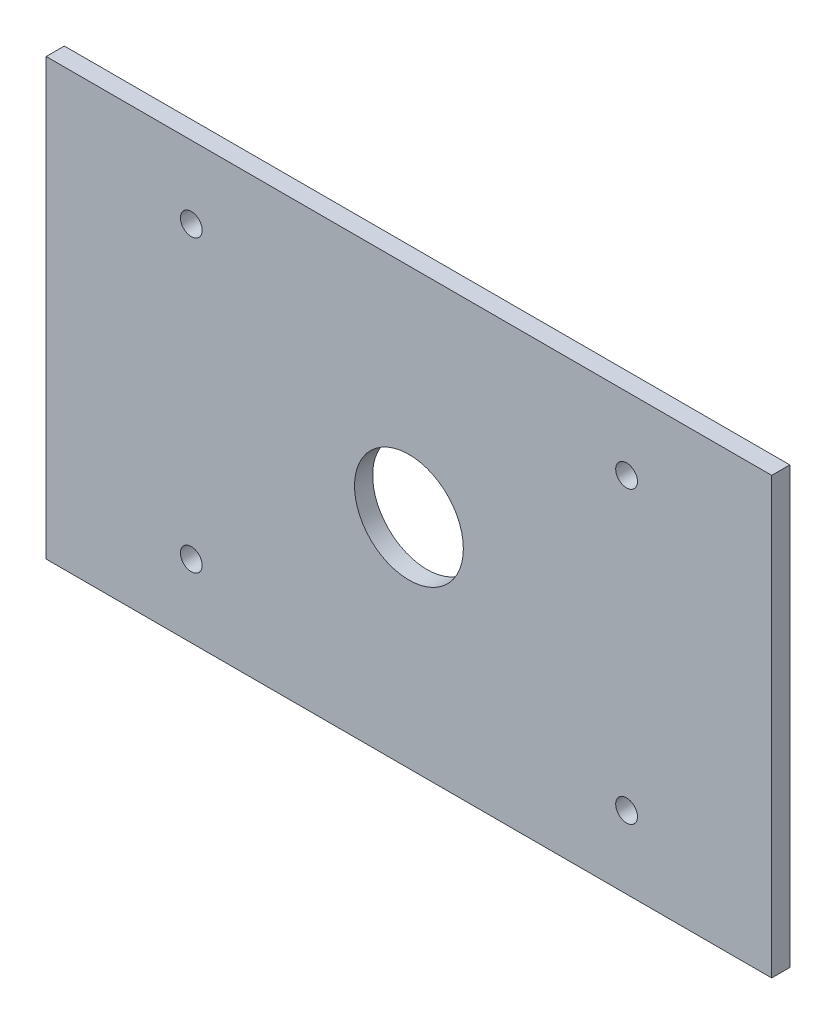
SolidWorks part; units mm, degrees
ref_plane "Front Plane" through (0, 0, 0) normal (0, 0, 1) x (1, 0, 0)
ref_plane "Top Plane" through (0, 0, 0) normal (0, 1, 0) x (1, 0, 0)
ref_plane "Right Plane" through (0, 0, 0) normal (1, 0, 0) x (0, 0, -1)
sketch "Sketch1" plane through (0, 0, 0) normal (0, 0, 1) x (1, 0, 0)
  line L1 (63.5, -38.1) -> (-63.5, -38.1)
  line L2 (63.5, -38.1) -> (63.5, 38.1)
  line L3 (63.5, 38.1) -> (-63.5, 38.1)
  line L4 (-63.5, -38.1) -> (-63.5, 38.1)
  line L5 (63.5, -38.1) -> (-63.5, 38.1) construction
  line L6 (63.5, 38.1) -> (-63.5, -38.1) construction
  point P0 (0, 0)
  dimension "D1" = 127
  dimension "D2" = 76.2
extrude "Boss-Extrude1" add sketch "Sketch1" along normal blind 3.175
sketch "Sketch2" plane through (0, 0, 3.175) normal (0, 0, 1) x (1, 0, 0)
  circle A0 centre (0, 0) radius 9.525
  dimension "D1" = 19.05
extrude "Boss-Extrude2" add sketch "Sketch2" along normal blind 12.7 and the other way blind 25.4
hole_wizard "1/2-13 Tapped Hole3" positions "Sketch10" profile "Sketch11" tap size "1/2-13" standard "ANSI Inch" end condition through all
sketch "Sketch10" plane through (0, 0, 15.875) normal (0, 0, 1) x (1, 0, 0)
  point P0 (0, 0)
sketch "Sketch11" plane through (0, 0, 15.875) normal (1, 0, 0) x (0, -1, 0)
  line L0 (0, 0) -> (0, 38.1)
  line L1 (0, 38.1) -> (5.842, 38.1)
  line L2 (5.842, 38.1) -> (5.842, 0)
  line L5 (5.842, 0) -> (0, 0)
  line L11 (0, -6.35) -> (0, 107.95) construction
  dimension "Thru Tap Drill Dia." = 11.684
  dimension "Thru Tap Drill Depth" = 38.1
cosmetic thread "Hole Thread1" parameters "D2"=12.7
thread "Thread2" pitch 1.9538 start angle 0, offset 0, length 30.32, pitch 1.9538, diameter 11.684
ref_plane "Plane2" through (-5.842, 0, 15.875) normal (0, -1, 0) x (-1, 0, 0)
sketch "Thread Profile2" plane through (-5.842, 0, 15.875) normal (0, -1, 0) x (-1, 0, 0)
  line L0 (0, 0) -> (0, 1.9538) construction
  line L1 (0, 0) -> (1.0576, 0.6106)
  line L2 (1.0576, 0.6106) -> (1.0576, 0.8548)
  line L3 (1.0576, 0.8548) -> (0, 1.4654)
  line L4 (1.0576, 0.7327) -> (0, 0.7327) construction
  line L11 (0, 0) -> (0, 1.4654)
  point P2 (0, 0)
  dimension "Pitch" = 1.9538
  dimension "Profile_Angle" = 60
  dimension "Profile_Land" = 0.2442
  dimension "Profile_Height" = 1.0576
sketch "Sketch12" plane through (0, 0, 3.175) normal (0, 0, 1) x (1, 0, 0)
  line L0 (-38.1, 25.4) -> (-38.1, -25.4) construction
  line L1 (-38.1, 25.4) -> (38.1, 25.4) construction
  circle A0 centre (-38.1, 25.4) radius 1.905
  circle A1 centre (-38.1, -25.4) radius 1.905
  circle A2 centre (38.1, -25.4) radius 1.905
  circle A3 centre (38.1, 25.4) radius 1.905
  point P8 (-38.1, 0)
  point P9 (0, 25.4)
  dimension "D1" = 3.81
  dimension "D2" = 38.1
  dimension "D3" = 25.4
extrude "Cut-Extrude1" cut sketch "Sketch12" against normal through all
sketch "Sketch13" plane through (0, 0, 15.875) normal (0, 0, 1) x (1, 0, 0)
  circle A0 centre (0, 0) radius 9.525
extrude "Cut-Extrude2" cut sketch "Sketch13" against normal blind 6.35
sketch "Sketch14" plane through (0, 0, 0) normal (1, 0, 0) x (0, 0, -1)
  line L1 (-9.069, 51.1355) -> (14.1401, 51.1355)
  line L2 (-9.069, 51.1355) -> (-9.069, -43.9652)
  line L3 (-9.069, -43.9652) -> (14.1401, -43.9652)
  line L4 (14.1401, 51.1355) -> (14.1401, -43.9652)
extrude "Cut-Extrude3" [suppressed] cut sketch "Sketch14" against normal through all and the other way through all
sketch "Sketch15" plane through (0, 0, 9.525) normal (0, 0, 1) x (1, 0, 0)
  circle A0 centre (0, 0) radius 9.525
extrude "Cut-Extrude4" cut sketch "Sketch15" against normal through all
